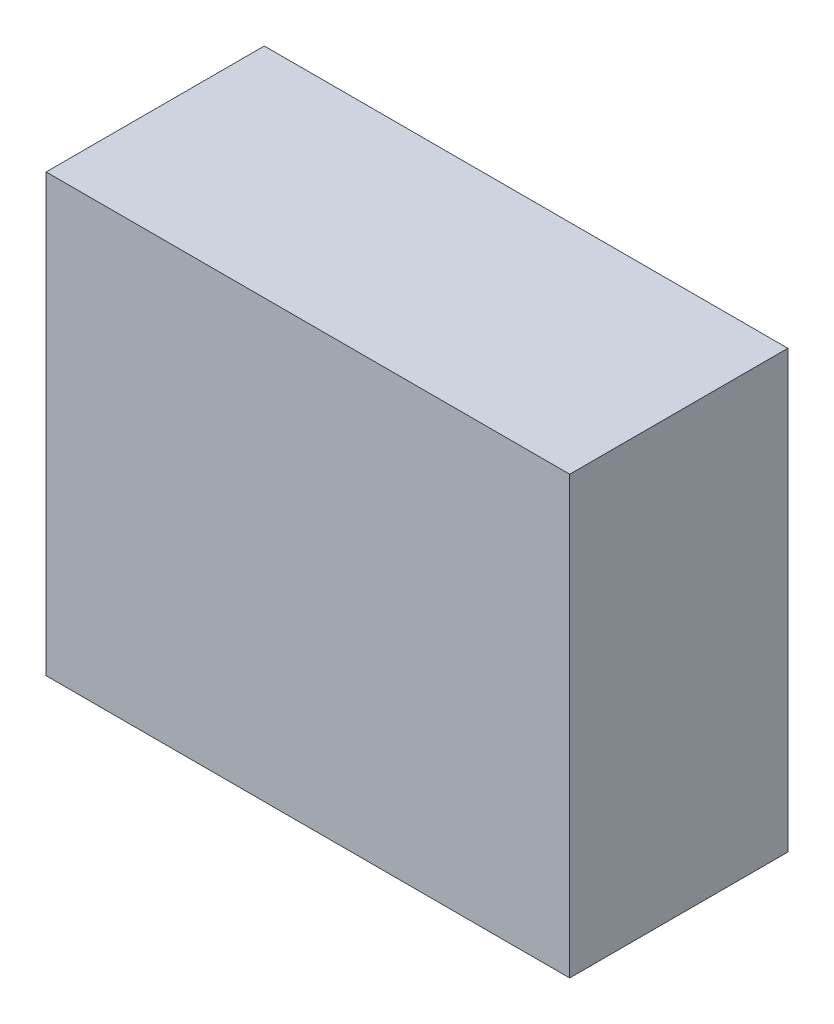
SolidWorks part; units mm, degrees
ref_plane "Front Plane" through (0, 0, 0) normal (0, 0, 1) x (1, 0, 0)
ref_plane "Top Plane" through (0, 0, 0) normal (0, 1, 0) x (1, 0, 0)
ref_plane "Right Plane" through (0, 0, 0) normal (1, 0, 0) x (0, 0, -1)
ref_plane "PL_Box_0_base" through (0, 0, 98) normal (0, 0, 1) x (1, 0, 0)
sketch "SK_Box_0" plane through (0, 0, 98) normal (0, 0, 1) x (1, 0, 0)
  line L0 (-68, -40) -> (28, -40)
  line L1 (28, -40) -> (28, 40)
  line L2 (28, 40) -> (-68, 40)
  line L3 (-68, 40) -> (-68, -40)
  dimension "P1" = 68
  dimension "P2" = 40
  dimension "P3" = 28
  dimension "P4" = 40
  dimension "P5" = 28
  dimension "P6" = 40
  dimension "P7" = 68
  dimension "P8" = 40
extrude "Box_0" add sketch "SK_Box_0" along normal blind 40
